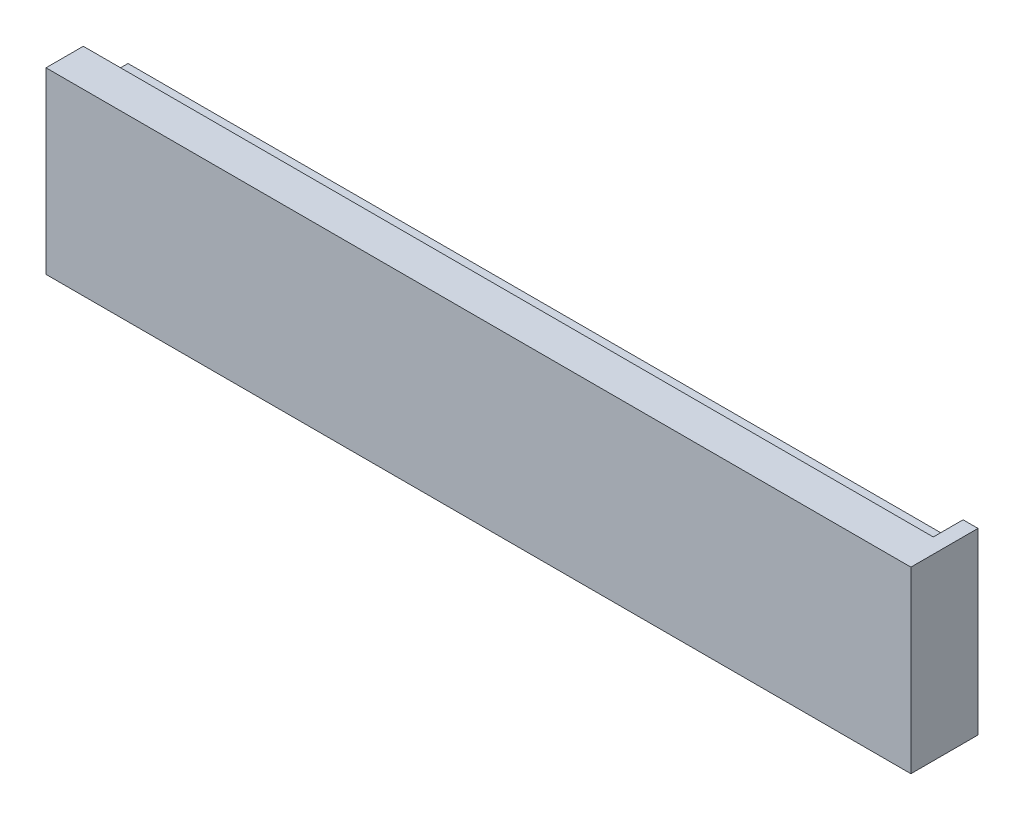
SolidWorks part; units mm, degrees
ref_plane "Front Plane" through (0, 0, 0) normal (1, 0, 0) x (0, 1, 0)
ref_plane "Top Plane" through (0, 0, 0) normal (0, 0, 1) x (0, 1, 0)
ref_plane "Right Plane" through (0, 0, 0) normal (0, 1, 0) x (-1, 0, 0)
sketch "Sketch1" plane through (0, 0, 0) normal (1, 0, 0) x (0, 1, 0)
  line L1 (0, 0) -> (17.78, 0)
  line L2 (0, 0) -> (0, 7.62)
  line L3 (0, 13.97) -> (17.78, 13.97)
  line L4 (17.78, 0) -> (17.78, 7.62)
  line L5 (17.78, 13.97) -> (24.13, 13.97)
  line L7 (17.78, 7.62) -> (24.13, 7.62)
  line L8 (24.13, 13.97) -> (24.13, 7.62)
  line L9 (0, 13.97) -> (-6.35, 13.97)
  line L11 (0, 7.62) -> (-6.35, 7.62)
  line L12 (-6.35, 13.97) -> (-6.35, 7.62)
  dimension "D1" = 17.78
  dimension "D2" = 13.97
  dimension "D3" = 6.35
  dimension "D4" = 6.35
  dimension "D5" = 6.35
  dimension "D6" = 6.35
extrude "Boss-Extrude1" add sketch "Sketch1" along normal blind 144.78
sketch "Sketch2" plane through (144.78, 0, 0) normal (1, 0, 0) x (0, 1, 0)
  line L0 (24.13, 7.62) -> (24.13, 13.97) construction
  line L1 (-6.35, 13.97) -> (24.13, 13.97)
  line L2 (-6.35, 13.97) -> (-6.35, 2.54)
  line L3 (-6.35, 2.54) -> (24.13, 2.54)
  line L4 (24.13, 13.97) -> (24.13, 2.54)
  line L6 (0, 0) -> (17.78, 0) construction
  dimension "D1" = 0
  dimension "D2" = 2.54
extrude "Boss-Extrude2" add sketch "Sketch2" along normal blind 2.54
